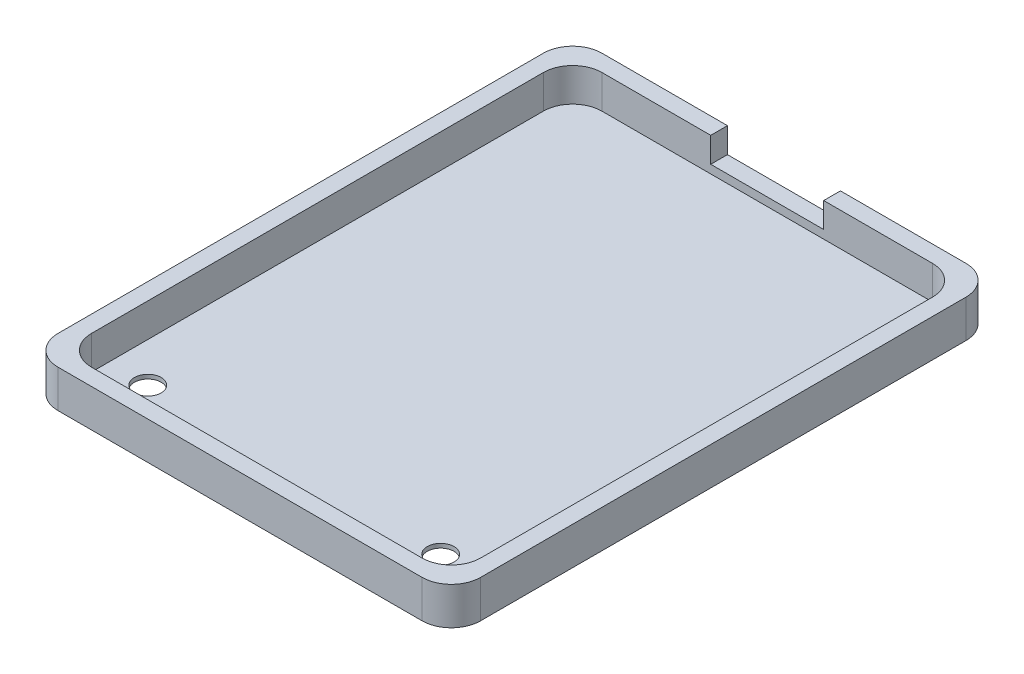
SolidWorks part; units mm, degrees
ref_plane "Alzado" through (0, 0, 0) normal (0, 0, 1) x (1, 0, 0)
ref_plane "Planta" through (0, 0, 0) normal (0, 1, 0) x (1, 0, 0)
ref_plane "Vista lateral" through (0, 0, 0) normal (1, 0, 0) x (0, 0, -1)
sketch "Sketch1" plane through (0, 0, 0) normal (0, 1, 0) x (1, 0, 0)
  line L1 (3.5, 0) -> (47, 0)
  line L2 (0, 3.5) -> (0, 61.5)
  line L3 (3.5, 65) -> (47, 65)
  line L4 (50.5, 3.5) -> (50.5, 61.5)
  arc A0 (47, 0) -> (50.5, 3.5) centre (47, 3.5) ccw
  arc A1 (3.5, 0) -> (0, 3.5) centre (3.5, 3.5) cw
  arc A2 (0, 61.5) -> (3.5, 65) centre (3.5, 61.5) cw
  arc A3 (47, 65) -> (50.5, 61.5) centre (47, 61.5) cw
  point P7 (50.5, 0)
  point P10 (0, 0)
  point P15 (50.5, 65)
  dimension "D3" = 3.5
  dimension "D1" = 50.5
  dimension "D2" = 65
extrude "Boss-Extrude1" add sketch "Sketch1" along normal blind 4.5
sketch "Sketch2" plane through (0, 4.5, 0) normal (0, 1, 0) x (1, 0, 0)
  line L0 (3.5, 0) -> (47, 0) construction
  line L1 (5.5, 2) -> (45, 2)
  line L2 (2, 5.5) -> (2, 59.5)
  line L3 (5.5, 63) -> (45, 63)
  line L4 (48.5, 5.5) -> (48.5, 59.5)
  line L5 (2, 2) -> (48.5, 63) construction
  line L6 (2, 63) -> (48.5, 2) construction
  line L7 (47, 65) -> (3.5, 65) construction
  line L8 (50.5, 3.5) -> (50.5, 61.5) construction
  line L9 (0, 61.5) -> (0, 3.5) construction
  arc A0 (5.5, 2) -> (2, 5.5) centre (5.5, 5.5) cw
  arc A1 (45, 2) -> (48.5, 5.5) centre (45, 5.5) ccw
  arc A2 (2, 59.5) -> (5.5, 63) centre (5.5, 59.5) cw
  arc A3 (45, 63) -> (48.5, 59.5) centre (45, 59.5) cw
  point P0 (25.25, 32.5)
  dimension "D5" = 3.5
  dimension "D1" = 2
  dimension "D2" = 2
  dimension "D3" = 2
  dimension "D4" = 2
extrude "Cut-Extrude1" cut sketch "Sketch2" against normal blind 4
sketch "Sketch3" plane through (0, 0, -65) normal (0, 0, -1) x (-1, 0, 0)
  line L0 (-47, 0) -> (-3.5, 0) construction
  line L6 (-32, 1.5) -> (-18.5, 1.5)
  line L7 (-32, 1.5) -> (-32, 7.5)
  line L8 (-32, 7.5) -> (-18.5, 7.5)
  line L9 (-18.5, 1.5) -> (-18.5, 7.5)
  line L10 (-25.25, 4.5) -> (-25.25, 0) construction
  line L11 (-47, 4.5) -> (-3.5, 4.5) construction
  line L12 (-32, 1.5) -> (-18.5, 7.5) construction
  line L13 (-32, 7.5) -> (-18.5, 1.5) construction
  dimension "D1" = 1.5
  dimension "D2" = 13.5
extrude "Cut-Extrude3" cut sketch "Sketch3" against normal blind 15
sketch "Sketch4" plane through (0, 0.5, 0) normal (0, 1, 0) x (1, 0, 0)
  line L0 (25.25, 63) -> (25.25, 2) construction
  line L1 (32, 63) -> (18.5, 63) construction
  line L2 (5.5, 2) -> (45, 2) construction
  line L3 (25.25, 7.5) -> (6.7246, 7.5) construction
  line L4 (5.5, 2) -> (45, 2) construction
  circle A0 centre (6.7246, 7.5) radius 1.6
  circle A1 centre (41.7246, 7.5) radius 1.6
  dimension "D2" = 3.2
  dimension "D3" = 3.2
  dimension "D1" = 5.5
  dimension "D4" = 35
extrude "Cut-Extrude4" cut sketch "Sketch4" against normal blind 40
